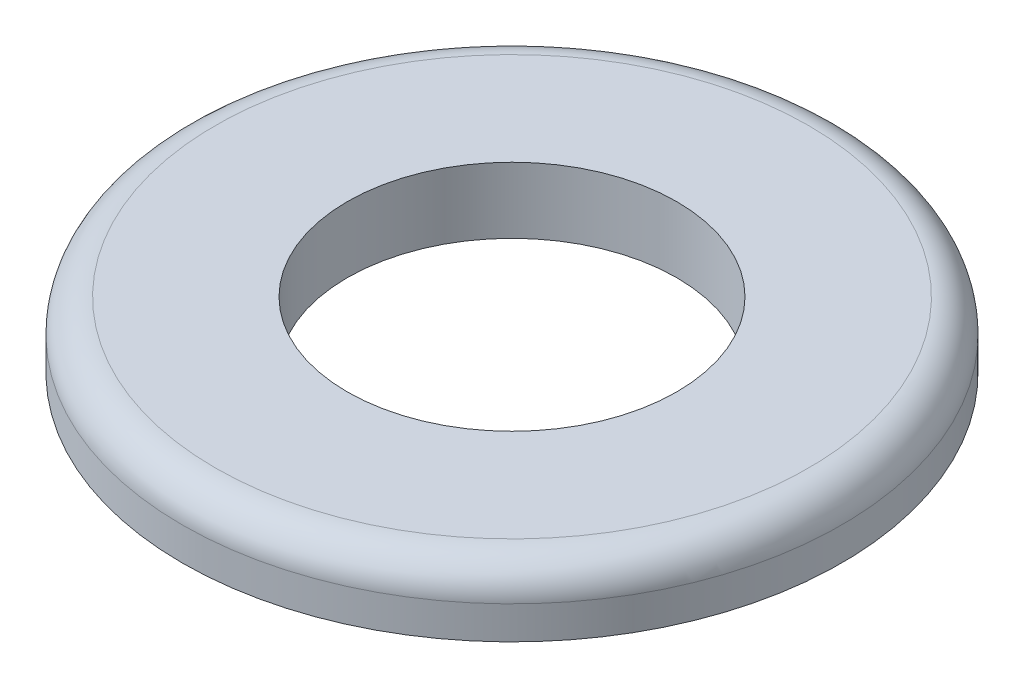
SolidWorks part; units mm, degrees
ref_plane "前视基准面" through (0, 0, 0) normal (0, 0, 1) x (1, 0, 0)
ref_plane "上视基准面" through (0, 0, 0) normal (0, 1, 0) x (1, 0, 0)
ref_plane "右视基准面" through (0, 0, 0) normal (1, 0, 0) x (0, 0, -1)
other "Configuration Table"
sketch "草图1" plane through (0, 0, 0) normal (0, 1, 0) x (1, 0, 0)
  circle A0 centre (0, 0) radius 2.5
  circle A1 centre (0, 0) radius 5
  dimension "D1" = 5
  dimension "D2" = 10
extrude "凸台-拉伸1" add sketch "草图1" along normal blind 1
fillet "圆角1" radius 0.5 1 edges at (0, 1, 5)
